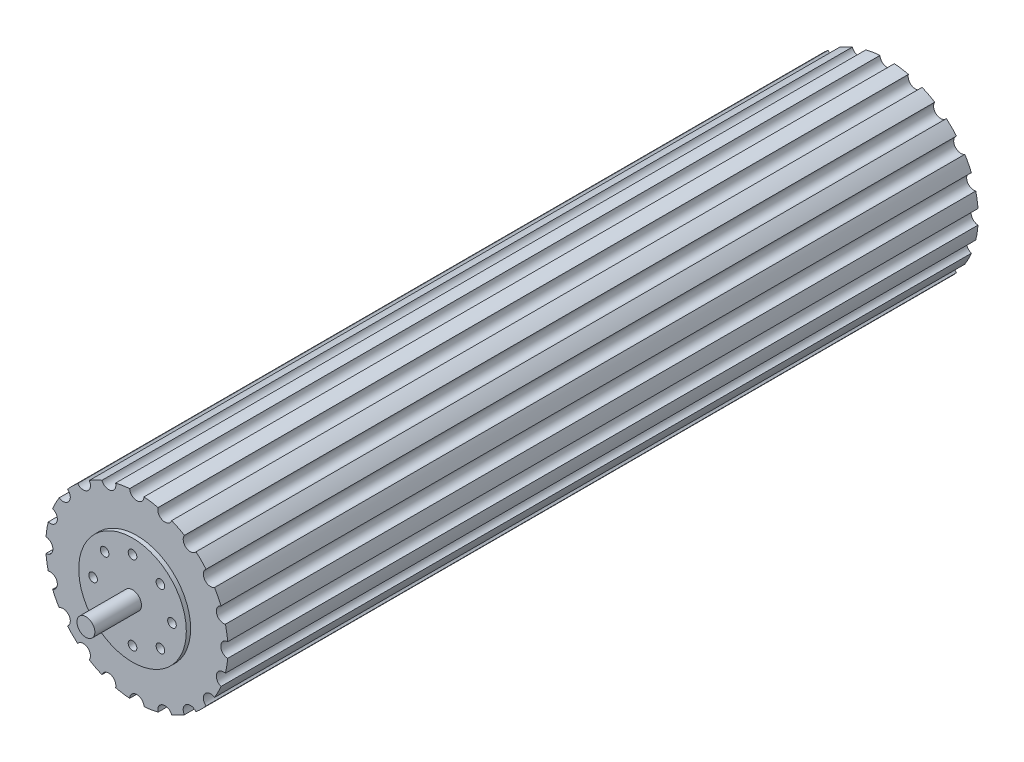
SolidWorks part; units mm, degrees
ref_plane "Front Plane" through (0, 0, 0) normal (0, 0, 1) x (1, 0, 0)
ref_plane "Top Plane" through (0, 0, 0) normal (0, 1, 0) x (1, 0, 0)
ref_plane "Right Plane" through (0, 0, 0) normal (1, 0, 0) x (0, 0, -1)
sketch "Sketch1" plane through (0, 0, 0) normal (0, 0, 1) x (1, 0, 0)
  circle A0 centre (0, 0) radius 127
  circle A1 centre (0, 0) radius 12.5
  dimension "D1" = 254
  dimension "D2" = 25
extrude "Boss-Extrude1" add sketch "Sketch1" along normal blind 1046
ref_plane "Plane1" through (0, 0, 533) normal (0, 0, 1) x (1, 0, 0)
sketch "Sketch3" plane through (0, 0, 533) normal (0, 0, 1) x (1, 0, 0)
  circle A0 centre (0, 0) radius 12.5
  dimension "D1" = 25
extrude "Boss-Extrude2" add sketch "Sketch3" along normal mid plane 1168
sketch "Sketch4" plane through (0, 0, 1046) normal (0, 0, 1) x (1, 0, 0)
  circle A0 centre (0, 0) radius 75
  circle A1 centre (0, 0) radius 12.5 construction
  circle A2 centre (0, 0) radius 12.5
  dimension "D1" = 150
extrude "Boss-Extrude4" add sketch "Sketch4" along normal blind 6
sketch "Sketch6" plane through (0, 0, 0) normal (0, 0, -1) x (-1, 0, 0)
  circle A0 centre (0, 0) radius 75
  dimension "D1" = 150
extrude "Boss-Extrude5" add sketch "Sketch6" along normal blind 6
sketch "Sketch7" plane through (0, 0, -6) normal (0, 0, -1) x (-1, 0, 0)
  circle A0 centre (0, 0) radius 55 construction
  circle A1 centre (0, 55) radius 6
  circle A2 centre (38.8909, 38.8909) radius 6
  circle A3 centre (55, 0) radius 6
  circle A4 centre (38.8909, -38.8909) radius 6
  circle A5 centre (0, -55) radius 6
  circle A6 centre (-38.8909, -38.8909) radius 6
  circle A7 centre (-55, 0) radius 6
  circle A8 centre (-38.8909, 38.8909) radius 6
  point P22 (0, 0)
  dimension "D1" = 110
  dimension "D2" = 12
  dimension "D3" = 8
extrude "Cut-Extrude1" cut sketch "Sketch7" against normal through all both and the other way through all
sketch "Sketch8" plane through (0, 0, 0) normal (0, 0, -1) x (-1, 0, 0)
  circle A0 centre (0, 127) radius 10
  circle A1 centre (0, 0) radius 127 construction
  circle A2 centre (39.2452, 120.7842) radius 10
  circle A3 centre (74.6487, 102.7452) radius 10
  circle A4 centre (102.7452, 74.6487) radius 10
  circle A5 centre (120.7842, 39.2452) radius 10
  circle A6 centre (127, 0) radius 10
  circle A7 centre (120.7842, -39.2452) radius 10
  circle A8 centre (102.7452, -74.6487) radius 10
  circle A9 centre (74.6487, -102.7452) radius 10
  circle A10 centre (39.2452, -120.7842) radius 10
  circle A11 centre (0, -127) radius 10
  circle A12 centre (-39.2452, -120.7842) radius 10
  circle A13 centre (-74.6487, -102.7452) radius 10
  circle A14 centre (-102.7452, -74.6487) radius 10
  circle A15 centre (-120.7842, -39.2452) radius 10
  circle A16 centre (-127, 0) radius 10
  circle A17 centre (-120.7842, 39.2452) radius 10
  circle A18 centre (-102.7452, 74.6487) radius 10
  circle A19 centre (-74.6487, 102.7452) radius 10
  circle A20 centre (-39.2452, 120.7842) radius 10
  point P45 (0, 0)
  dimension "D1" = 20
  dimension "D2" = 20
extrude "Cut-Extrude2" cut sketch "Sketch8" against normal through all both and the other way through all
